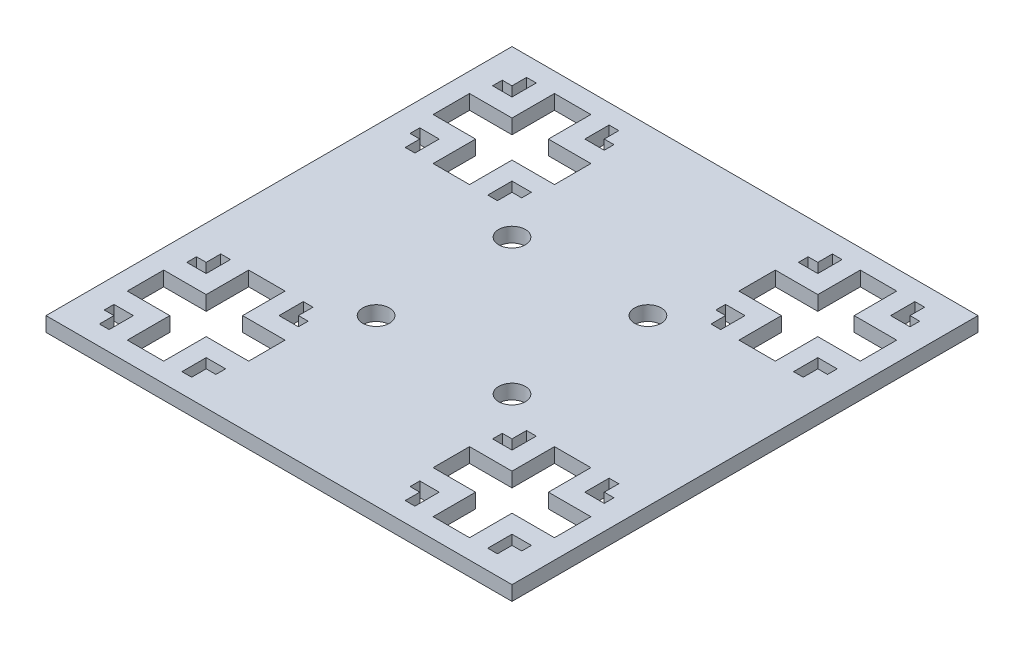
SolidWorks part; units mm, degrees
ref_plane "前视基准面" through (0, 0, 0) normal (0, 0, 1) x (1, 0, 0)
ref_plane "上视基准面" through (0, 0, 0) normal (0, 1, 0) x (1, 0, 0)
ref_plane "右视基准面" through (0, 0, 0) normal (1, 0, 0) x (0, 0, -1)
sketch "草图1" plane through (0, 0, 0) normal (0, 1, 0) x (1, 0, 0)
  line L1 (-48, 48) -> (48, 48)
  line L2 (-48, 48) -> (-48, -48)
  line L3 (-48, -48) -> (48, -48)
  line L4 (48, 48) -> (48, -48)
  line L5 (-48, 48) -> (48, -48) construction
  line L6 (-48, -48) -> (48, 48) construction
  point P0 (0, 0)
  dimension "D1" = 96
  dimension "D2" = 96
extrude "凸台-拉伸1" add sketch "草图1" along normal blind 3
sketch "草图3" plane through (0, 3, 0) normal (0, 1, 0) x (1, 0, 0)
  line L0 (-1000, 0) -> (49000, 0) construction
  line L1 (0, -1000) -> (0, 49000) construction
  line L2 (-27.75, 35.25) -> (-19, 35.25)
  line L3 (-44, 27.75) -> (-35.25, 27.75)
  line L4 (-44, 27.75) -> (-44, 35.25)
  line L5 (-44, 35.25) -> (-35.25, 35.25)
  line L6 (-19, 27.75) -> (-19, 35.25)
  line L7 (-44, 27.75) -> (-19, 35.25) construction
  line L8 (-44, 35.25) -> (-19, 27.75) construction
  line L9 (-35.25, 44) -> (-27.75, 44)
  line L10 (-35.25, 44) -> (-35.25, 35.25)
  line L11 (-35.25, 19) -> (-27.75, 19)
  line L12 (-27.75, 44) -> (-27.75, 35.25)
  line L13 (-35.25, 44) -> (-27.75, 19) construction
  line L14 (-35.25, 19) -> (-27.75, 44) construction
  line L15 (-27.75, 27.75) -> (-27.75, 19)
  line L16 (-27.75, 27.75) -> (-19, 27.75)
  line L17 (-35.25, 27.75) -> (-35.25, 19)
  line L18 (-1031.5, 31.5) -> (48968.5, 31.5) construction
  line L19 (-31.5, -968.5) -> (-31.5, 49031.5) construction
  line L20 (-41, 44) -> (-39, 44)
  line L21 (-39, 44) -> (-39, 39)
  line L22 (-39, 39) -> (-43, 39)
  line L23 (-43, 39) -> (-43, 41)
  line L24 (-43, 41) -> (-41, 41)
  line L25 (-41, 41) -> (-41, 44)
  line L26 (-22, 41) -> (-22, 44)
  line L27 (-20, 41) -> (-22, 41)
  line L28 (-20, 39) -> (-20, 41)
  line L29 (-24, 39) -> (-20, 39)
  line L30 (-24, 44) -> (-24, 39)
  line L31 (-22, 44) -> (-24, 44)
  line L32 (-22, 19) -> (-24, 19)
  line L33 (-24, 19) -> (-24, 24)
  line L34 (-24, 24) -> (-20, 24)
  line L35 (-20, 24) -> (-20, 22)
  line L36 (-20, 22) -> (-22, 22)
  line L37 (-22, 22) -> (-22, 19)
  line L38 (-41, 22) -> (-41, 19)
  line L39 (-43, 22) -> (-41, 22)
  line L40 (-43, 24) -> (-43, 22)
  line L41 (-39, 24) -> (-43, 24)
  line L42 (-39, 19) -> (-39, 24)
  line L43 (-41, 19) -> (-39, 19)
  circle A0 centre (-14, 14) radius 2.75
  point P7 (-31.5, 31.5)
  point P12 (-31.5, 31.5)
  dimension "D1" = 5.5
  dimension "D2" = 28
  dimension "D3" = 28
  dimension "D4" = 7.5
  dimension "D5" = 7.5
  dimension "D6" = 25
  dimension "D7" = 25
  dimension "D8" = 5
  dimension "D9" = 5
  dimension "D10" = 2
  dimension "D11" = 2
  dimension "D12" = 15
  dimension "D13" = 15
  dimension "D14" = 4
  dimension "D15" = 5
extrude "切除-拉伸1" cut sketch "草图3" against normal up to next
mirror "镜向1" about plane through (0, 0, 0) normal (1, 0, 0) of "切除-拉伸1"
mirror "镜向2" about plane through (0, 0, 0) normal (0, 0, 1) of "镜向1", "切除-拉伸1"
